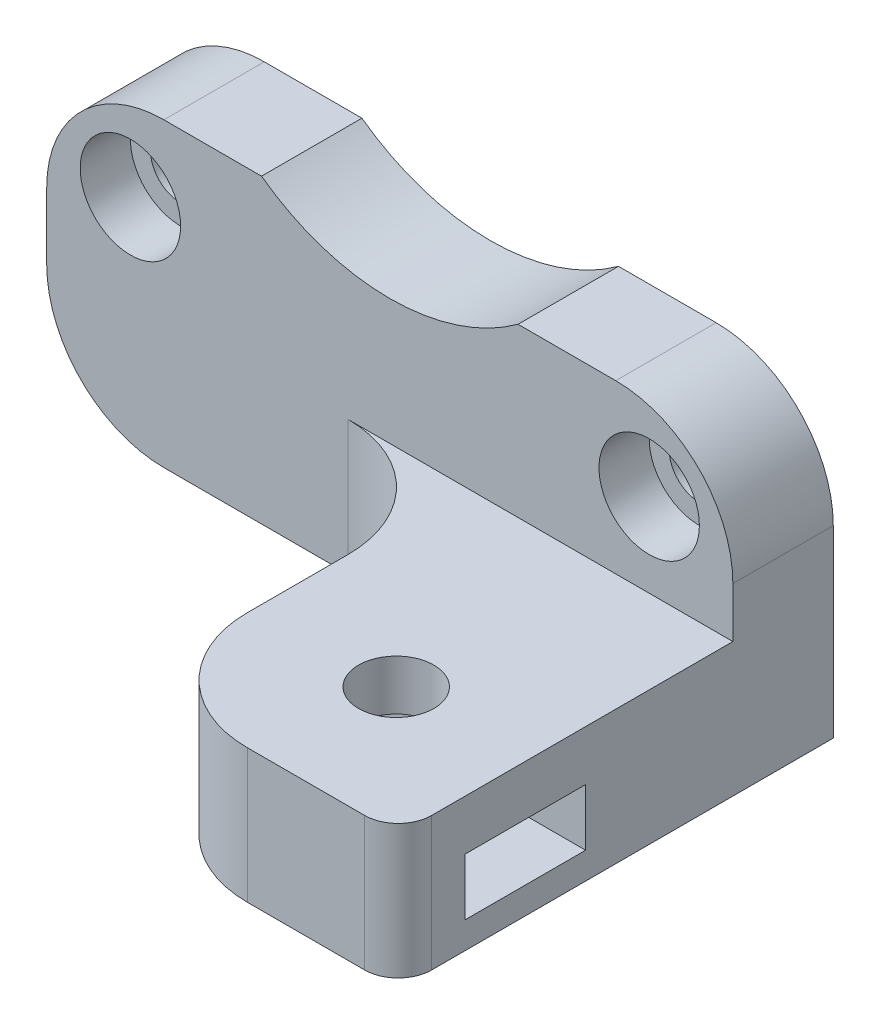
SolidWorks part; units mm, degrees
ref_plane "Front Plane" through (0, 0, 0) normal (0, 0, 1) x (1, 0, 0)
ref_plane "Top Plane" through (0, 0, 0) normal (0, 1, 0) x (1, 0, 0)
ref_plane "Right Plane" through (0, 0, 0) normal (1, 0, 0) x (0, 0, -1)
sketch "Sketch2" plane through (0, 0, 0) normal (1, 0, 0) x (0, 0, -1)
  line L0 (0, 0) -> (0, 10)
  line L1 (0, 10) -> (6, 10)
  line L2 (6, 10) -> (6, -8)
  line L3 (6, -8) -> (-20, -8)
  line L4 (-20, -8) -> (-20, 0)
  line L5 (-20, 0) -> (0, 0)
  dimension "D1" = 8
  dimension "D2" = 20
  dimension "D3" = 10
  dimension "D4" = 6
extrude "Boss-Extrude2" add sketch "Sketch2" along normal blind 41 contours L0 L1 L2 L3 L4 L5
sketch "Sketch3" plane through (0, 0, 0) normal (0, 0, 1) x (1, 0, 0)
  line L0 (5, 5) -> (36, 5) construction
  line L1 (20.5, 5) -> (20.5, 10) construction
  line L2 (20.5, 10) -> (20.5, 20.5) construction
  line L3 (41, 10) -> (0, 10) construction
  circle A0 centre (5, 5) radius 1.8
  circle A1 centre (20.5, 20.5) radius 13
  circle A2 centre (36, 5) radius 1.8
  dimension "D1" = 31
  dimension "D3" = 3.6
  dimension "D5" = 26
  dimension "D2" = 5
  dimension "D4" = 10.5
extrude "Cut-Extrude1" cut sketch "Sketch3" against normal through all contours A0 | A2 | A1
hole_wizard "M4 Clearance Hole1" positions "3DSketch1" profile "Sketch5" hole size "M4" standard "ANSI Metric" end condition through all
sketch3d "3DSketch1"
  line L2 (41, 0, 20) -> (41, 0, 0) construction
  line L3 (41, 0, 0) -> (0, 0, 0) construction
  point P0 (33.2838, 0, 12.4)
  dimension "D1" = 7.7162
  dimension "D2" = 12.4
sketch "Sketch5" plane through (33.2838, 0, 12.4) normal (1, 0, 0) x (0, 0, 1)
  line L0 (0, 0) -> (0, 8)
  line L1 (0, 8) -> (2.25, 8)
  line L2 (2.25, 8) -> (2.25, 0)
  line L5 (2.25, 0) -> (0, 0)
  line L11 (0, -6.35) -> (0, 107.95) construction
  dimension "Thru Hole Dia." = 4.5
  dimension "Thru Hole Depth" = 8
sketch "Sketch6" plane through (0, 0, 0) normal (0, 0, 1) x (1, 0, 0)
  circle A0 centre (5, 5) radius 3
  circle A1 centre (36, 5) radius 3
  dimension "D1" = 6
extrude "Cut-Extrude2" cut sketch "Sketch6" against normal blind 3
sketch "Sketch7" plane through (0, 0, 0) normal (0, 1, 0) x (1, 0, 0)
  line L0 (30.8838, -12.4) -> (33.2838, -12.4) construction
  line L1 (32.9623, -16) -> (35.0407, -12.4)
  line L2 (35.0407, -12.4) -> (32.9623, -8.8)
  line L3 (32.9623, -8.8) -> (28.8053, -8.8)
  line L4 (28.8053, -8.8) -> (26.7269, -12.4)
  line L5 (26.7269, -12.4) -> (28.8053, -16)
  line L6 (28.8053, -16) -> (32.9623, -16)
  line L7 (32.9623, -8.8) -> (44.9623, -8.8)
  line L8 (44.9623, -8.8) -> (44.9623, -16)
  line L9 (44.9623, -16) -> (32.9623, -16)
  circle A0 centre (30.8838, -12.4) radius 3.6 construction
  circle A3 centre (33.2838, -12.4) radius 2.25 construction
  dimension "D1" = 2.4
  dimension "D2" = 7.2
  dimension "D3" = 12
extrude "Cut-Extrude3" cut sketch "Sketch7" against normal blind 3.4 from offset 3 offset against normal yes
fillet "Fillet3" radius 2 1 edges at (41, -4, 20)
sketch "Sketch9" plane through (0, 0, 0) normal (0, 1, 0) x (1, 0, 0)
  line L0 (39, -20) -> (0, -20) construction
  line L1 (0, 0) -> (25, 0)
  line L2 (0, 0) -> (0, -20)
  line L3 (0, -20) -> (25, -20)
  line L4 (25, 0) -> (25, -20)
  dimension "D1" = 25
extrude "Cut-Extrude5" cut sketch "Sketch9" against normal through all
fillet "Fillet5" radius 7 5 edges at (25, -4, 0) (25, -4, 20) (41, 10, -3) (0, -8, -3) (0, 10, -3)
